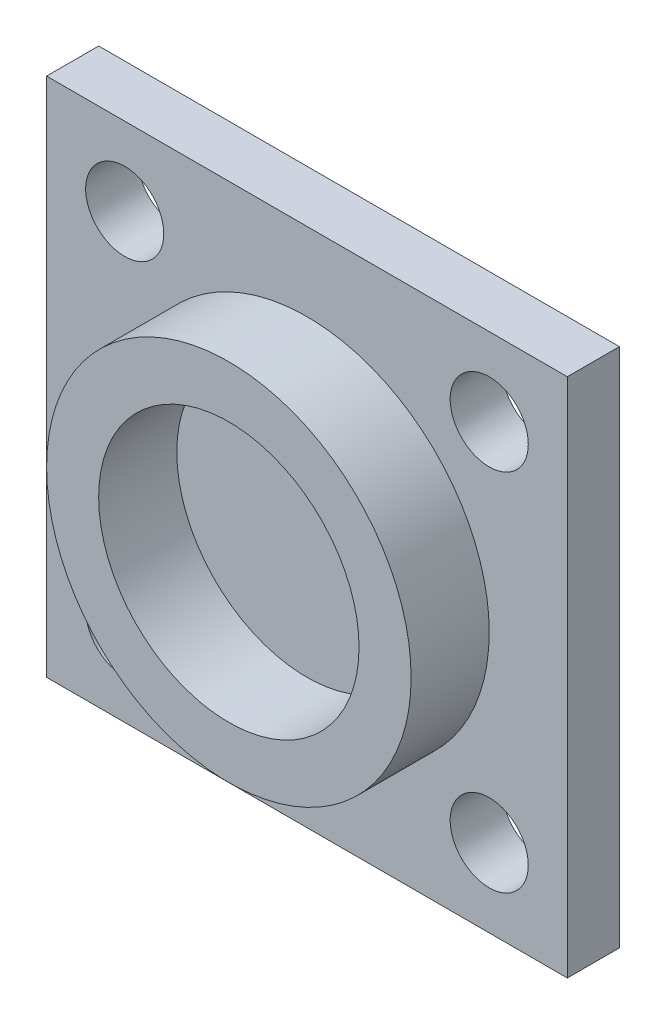
SolidWorks part; units mm, degrees
ref_plane "前视基准面" through (0, 0, 0) normal (0, 0, 1) x (1, 0, 0)
ref_plane "上视基准面" through (0, 0, 0) normal (0, 1, 0) x (1, 0, 0)
ref_plane "右视基准面" through (0, 0, 0) normal (1, 0, 0) x (0, 0, -1)
other "Configuration Table"
sketch "草图1" plane through (0, 0, 0) normal (0, 0, 1) x (1, 0, 0)
  line L1 (-10, 10) -> (10, 10)
  line L2 (-10, 10) -> (-10, -10)
  line L3 (-10, -10) -> (10, -10)
  line L4 (10, 10) -> (10, -10)
  line L5 (-10, 10) -> (10, -10) construction
  line L6 (-10, -10) -> (10, 10) construction
  circle A0 centre (-7, 7) radius 1.5
  circle A1 centre (7, 7) radius 1.5
  circle A2 centre (7, -7) radius 1.5
  circle A3 centre (-7, -7) radius 1.5
  point P0 (0, 0)
  point P17 (0, 0)
  dimension "D3" = 3
  dimension "D1" = 20
  dimension "D2" = 20
  dimension "D4" = 4
extrude "凸台-拉伸1" add sketch "草图1" along normal blind 2
sketch "草图2" plane through (0, 0, 2) normal (0, 0, 1) x (1, 0, 0)
  circle A0 centre (0, 0) radius 5
  circle A1 centre (0, 0) radius 7
extrude "凸台-拉伸2" add sketch "草图2" along normal blind 3
